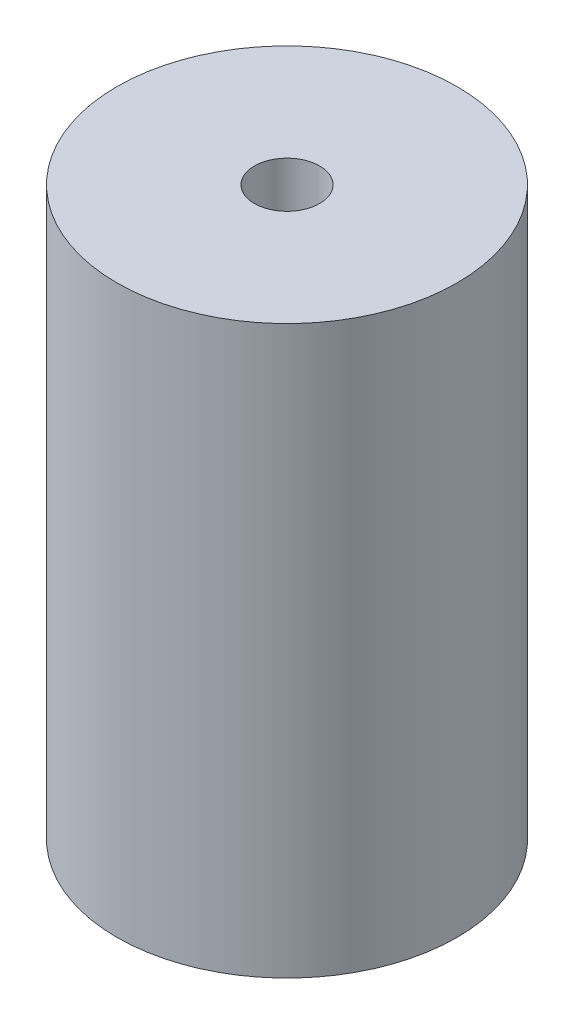
SolidWorks part; units mm, degrees
ref_plane "Front Plane" through (0, 0, 0) normal (0, 0, 1) x (1, 0, 0)
ref_plane "Top Plane" through (0, 0, 0) normal (0, 1, 0) x (1, 0, 0)
ref_plane "Right Plane" through (0, 0, 0) normal (1, 0, 0) x (0, 0, -1)
sketch "Sketch1" plane through (0, 0, 0) normal (0, 1, 0) x (1, 0, 0)
  circle A0 centre (0, 0) radius 6
  dimension "D1" = 12
extrude "Boss-Extrude1" add sketch "Sketch1" along normal blind 20
sketch "Sketch2" plane through (0, 20, 0) normal (0, 1, 0) x (1, 0, 0)
  circle A0 centre (0, 0) radius 1.15
  dimension "D1" = 2.3
extrude "Cut-Extrude1" cut sketch "Sketch2" against normal blind 5
sketch "Sketch3" plane through (0, 0, 0) normal (0, -1, 0) x (1, 0, 0)
  circle A0 centre (0, 0) radius 2.5
  dimension "D1" = 5
extrude "Cut-Extrude2" cut sketch "Sketch3" against normal blind 5
